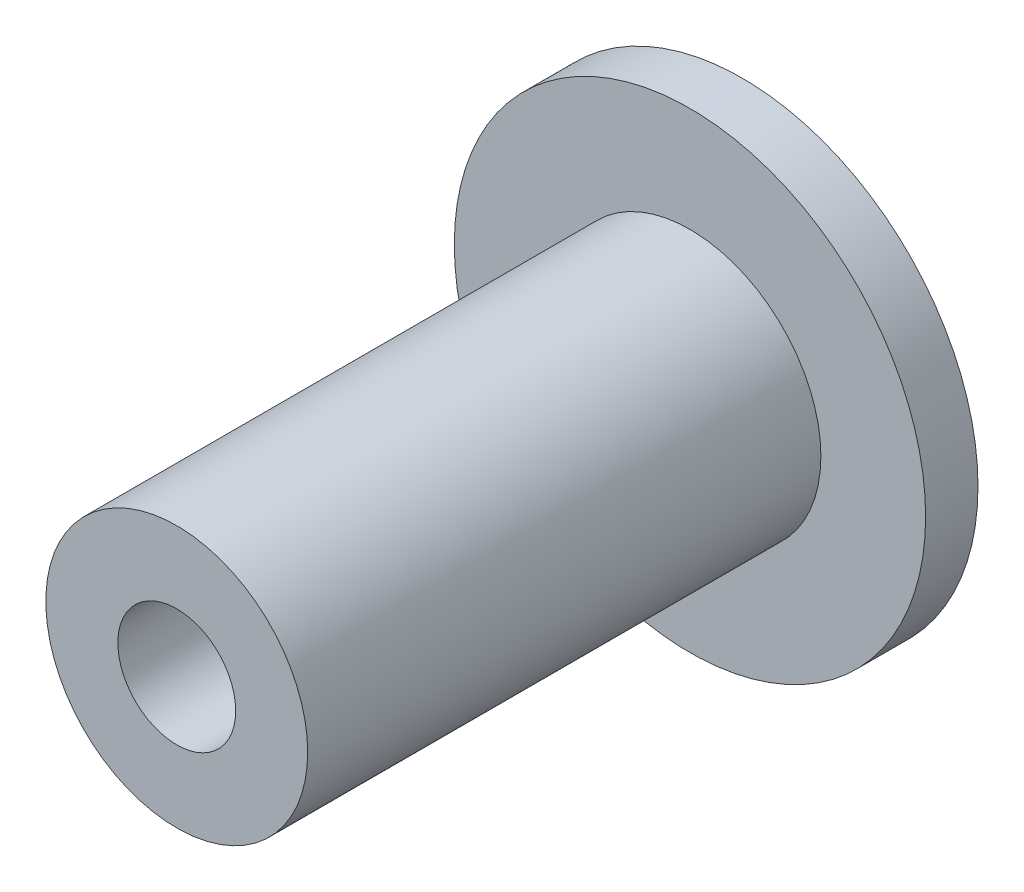
SolidWorks part; units mm, degrees
material "PETG"
ref_plane "Alzado" through (0, 0, 0) normal (0, 0, 1) x (1, 0, 0)
ref_plane "Planta" through (0, 0, 0) normal (0, 1, 0) x (1, 0, 0)
ref_plane "Vista lateral" through (0, 0, 0) normal (1, 0, 0) x (0, 0, -1)
sketch "Croquis1" plane through (0, 0, 0) normal (0, 0, 1) x (1, 0, 0)
  circle A0 centre (0, 0) radius 5
  circle A1 centre (0, 0) radius 4.25
  dimension "D1" = 10
  dimension "D2" = 0.75
extrude "Saliente-Extruir1" add sketch "Croquis1" against normal blind 19.6
sketch "Croquis2" plane through (0, 0, -19.6) normal (0, 0, -1) x (-1, 0, 0)
  circle A0 centre (0, 0) radius 9
  circle A1 centre (0, 0) radius 4.25 construction
  circle A2 centre (0, 0) radius 4.25
  dimension "D1" = 18
extrude "Saliente-Extruir2" add sketch "Croquis2" along normal blind 2
sketch "Croquis3" plane through (0, 0, 0) normal (0, 0, 1) x (1, 0, 0)
  circle A1 centre (0, 0) radius 5
  circle A2 centre (0, 0) radius 5
  dimension "D1" = 0
extrude "Saliente-Extruir3" add sketch "Croquis3" against normal blind 5
sketch "Croquis4" plane through (0, 0, 0) normal (0, 0, 1) x (1, 0, 0)
  circle A0 centre (0, 0) radius 2.25
  dimension "D1" = 4.5
extrude "Cortar-Extruir1" cut sketch "Croquis4" against normal blind 6
sketch "Croquis5" plane through (0, 0, -21.6) normal (0, 0, -1) x (-1, 0, 0)
  circle A0 centre (0, 0) radius 4.25 construction
  circle A1 centre (0, 0) radius 4.25
extrude "Saliente-Extruir4" add sketch "Croquis5" against normal up to surface (16.6 mm away) up to face at (2.25, 0, -5)
